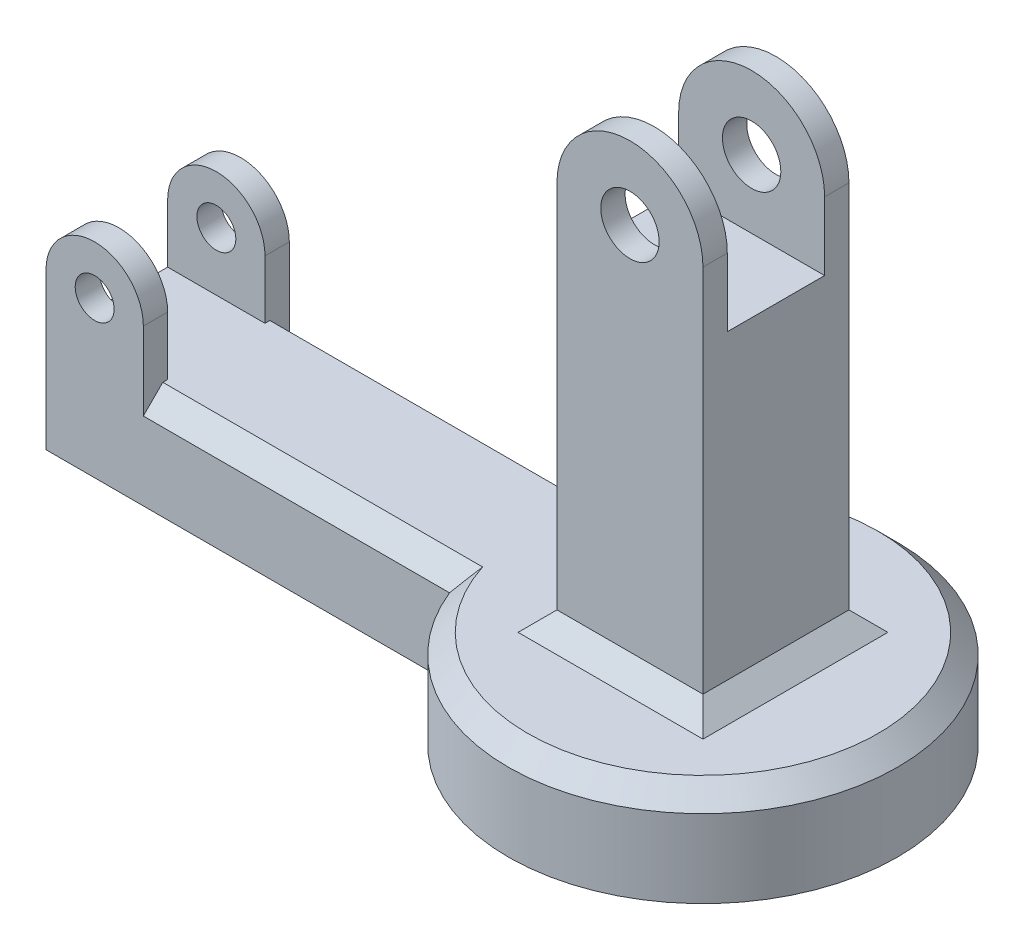
SolidWorks part; units mm, degrees
material "AISI 1020"
ref_plane "Front Plane" through (0, 0, 0) normal (0, 0, 1) x (1, 0, 0)
ref_plane "Top Plane" through (0, 0, 0) normal (0, 1, 0) x (1, 0, 0)
ref_plane "Right Plane" through (0, 0, 0) normal (1, 0, 0) x (0, 0, -1)
sketch "Sketch1" plane through (0, 0, 0) normal (0, 1, 0) x (1, 0, 0)
  circle A0 centre (0, 0) radius 100
  dimension "D1" = 200
extrude "Boss-Extrude1" add sketch "Sketch1" along normal blind 50
sketch "Sketch2" plane through (0, 50, 0) normal (0, 1, 0) x (1, 0, 0)
  line L1 (-300, 37.5) -> (0, 37.5)
  line L2 (-300, 37.5) -> (-300, -37.5)
  line L3 (-300, -37.5) -> (0, -37.5)
  line L4 (0, 37.5) -> (0, -37.5)
  dimension "D1" = 75
  dimension "D2" = 300
extrude "Boss-Extrude2" add sketch "Sketch2" against normal blind 50
sketch "Sketch3" plane through (0, 0, 0) normal (0, 0, 1) x (1, 0, 0)
  line L0 (-300, 50) -> (-300, 80)
  line L1 (-250, 80) -> (-250, 50)
  line L2 (-300, 50) -> (-92.7025, 50) construction
  line L3 (-250, 50) -> (-300, 50)
  line L4 (100, 50) -> (-92.7025, 50) construction
  line L5 (-37.5, 50) -> (37.5, 50)
  line L6 (-37.5, 50) -> (-37.5, 250)
  line L7 (-37.5, 250) -> (37.5, 250) construction
  line L8 (37.5, 50) -> (37.5, 250)
  line L9 (0, 0) -> (0, 50) construction
  arc A0 (-300, 80) -> (-250, 80) centre (-275, 80) cw
  arc A1 (-37.5, 250) -> (37.5, 250) centre (0, 250) cw
  circle A2 centre (-275, 80) radius 10
  circle A3 centre (0, 250) radius 15
  dimension "D1" = 50
  dimension "D5" = 20
  dimension "D6" = 30
  dimension "D2" = 75
  dimension "D3" = 200
  dimension "D4" = 30
extrude "Boss-Extrude3" add sketch "Sketch3" along normal mid plane 75
sketch "Sketch4" plane through (0, 0, 0) normal (0, 0, 1) x (1, 0, 0)
  line L0 (-37.5, 215) -> (37.5, 215)
  line L1 (-37.5, 250) -> (-37.5, 50) construction
  line L2 (37.5, 50) -> (37.5, 250) construction
  line L3 (100, 50) -> (-92.7025, 50) construction
  line L4 (-37.5, 215) -> (-37.5, 287.5)
  line L5 (37.5, 215) -> (37.5, 287.5)
  line L6 (37.5, 287.5) -> (-37.5, 287.5)
  line L7 (-300, 0) -> (-300, 80) construction
  line L8 (-300, 50) -> (-250, 50)
  line L9 (-300, 50) -> (-300, 105)
  line L10 (-300, 105) -> (-250, 105)
  line L11 (-250, 50) -> (-250, 105)
  line L12 (-250, 50) -> (-250, 80) construction
  line L13 (-250, 50) -> (-92.7025, 50) construction
  arc A0 (37.5, 250) -> (-37.5, 250) centre (0, 250) ccw construction
  arc A1 (-250, 80) -> (-300, 80) centre (-275, 80) ccw construction
  dimension "D1" = 165
  dimension "D2" = 0
extrude "Cut-Extrude2" cut sketch "Sketch4" against normal mid plane 50
chamfer "Chamfer1" distance 10 angle 45 3 edges at (100, 50, 0)
chamfer "Chamfer2" distance 10 angle 45 4 edges at (37.5, 50, 0) (0, 50, 37.5) (-37.5, 50, 0) (0, 50, -37.5)
equation "\"A\"= 100"
equation "\"B\"= 100"
equation "\"C\"= 100"
equation "\"D\"= 100"
equation "\"E\"= 100"
